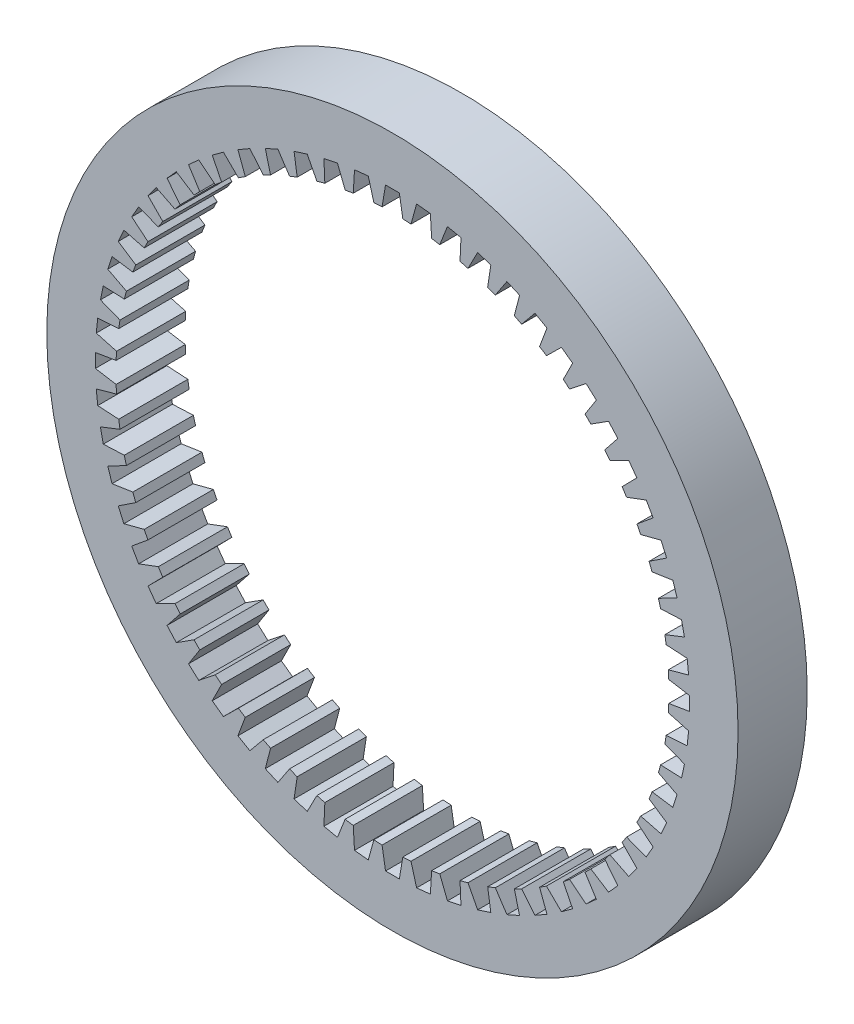
SolidWorks part; units mm, degrees
ref_plane "Front Plane" through (0, 0, 0) normal (0, 0, 1) x (1, 0, 0)
ref_plane "Top Plane" through (0, 0, 0) normal (0, 1, 0) x (1, 0, 0)
ref_plane "Right Plane" through (0, 0, 0) normal (1, 0, 0) x (0, 0, -1)
sketch "Sketch1" plane through (0, 0, 0) normal (0, 0, 1) x (1, 0, 0)
  circle A0 centre (0, 0) radius 50
  circle A1 centre (0, 0) radius 40
  dimension "D1" = 100
  dimension "D2" = 10
extrude "Boss-Extrude1" add sketch "Sketch1" along normal blind 10
sketch "Sketch2" plane through (0, 0, 0) normal (0, 0, -1) x (-1, 0, 0)
  line L0 (0, 40) -> (0, 45.6103) construction
  line L1 (1, 42.9719) -> (-1, 42.9719)
  line L2 (-1, 42.9719) -> (-1.5, 39.9719)
  line L3 (1, 42.9719) -> (1.5, 39.9719)
  circle A0 centre (0, 0) radius 40 construction
  circle A1 centre (0, 0) radius 40
  point P9 (-1.5, 39.9719)
  point P12 (0, 42.9719)
  circle M5 centre (0, 0) radius 40
  dimension "D1" = 1
  dimension "D2" = 3
  dimension "D3" = 1.5
extrude "Cut-Extrude1" cut sketch "Sketch2" against normal up to surface (10 mm away) contours L0 L1 L2 M5 | L0 A1 L3 L1 up to face at (50, 0, 10)
pattern_circular "CirPattern1" count 60 over 360 about axis through (0, 0, 0) along (0, 0, 1) of "Cut-Extrude1"
